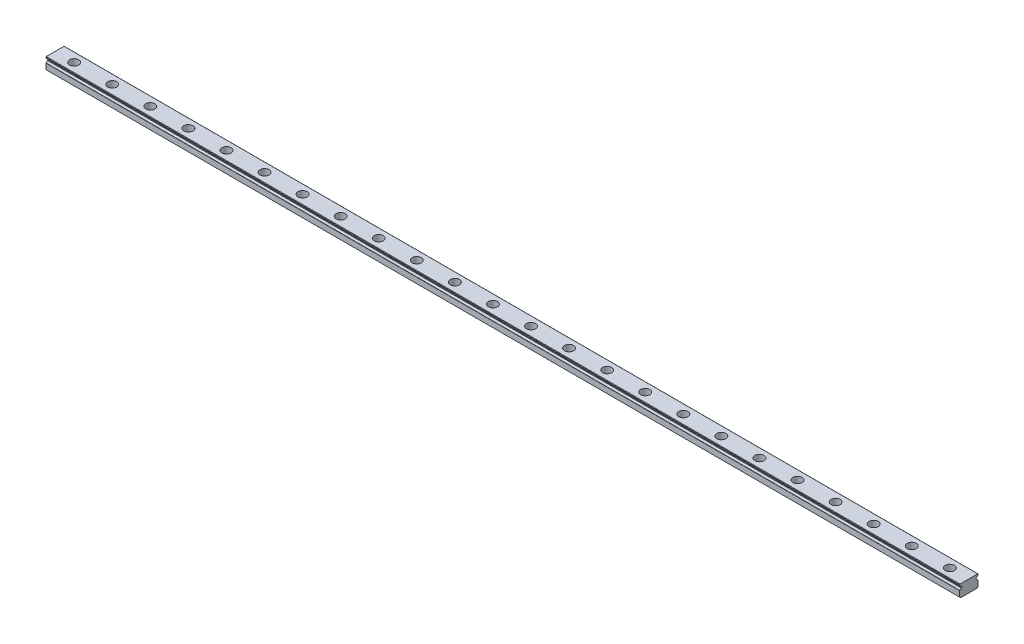
SolidWorks part; units mm, degrees
ref_plane "前视基准面" through (0, 0, 0) normal (0, 0, 1) x (1, 0, 0)
ref_plane "上视基准面" through (0, 0, 0) normal (0, 1, 0) x (1, 0, 0)
ref_plane "右视基准面" through (0, 0, 0) normal (1, 0, 0) x (0, 0, -1)
other "Configuration Table"
ref_plane "基准面1" through (0, 4, 0) normal (0, 1, 0) x (1, 0, 0)
sketch "草图1" plane through (0, 4, 0) normal (0, 1, 0) x (1, 0, 0)
  line L0 (300, -6) -> (300, 6)
  line L1 (300, 6) -> (-300, 6)
  line L2 (-300, 6) -> (-300, -6)
  line L3 (-300, -6) -> (300, -6)
extrude "凸台-拉伸1" add sketch "草图1" against normal blind 8
sketch "草图2" plane through (300, 0, 0) normal (1, 0, 0) x (0, 0, -1)
  line L0 (6, 1.51) -> (6, 2.01)
  line L1 (6, 2.01) -> (4.8, 2.01)
  line L2 (4.8, 1.51) -> (6, 1.51)
  arc A0 (4.8, 2.01) -> (4.8, 1.51) centre (4.8, 1.76) ccw
extrude "切除-拉伸1" cut sketch "草图2" against normal through all
sketch "草图3" plane through (300, 0, 0) normal (1, 0, 0) x (0, 0, -1)
  line L0 (6, 2.01) -> (6, 3.1111)
  line L1 (5.04, 2.01) -> (6, 2.01)
  arc A0 (6, 3.1111) -> (5.04, 2.01) centre (6.4382, 1.76) ccw
extrude "切除-拉伸2" cut sketch "草图3" against normal through all
sketch "草图4" plane through (300, 0, 0) normal (1, 0, 0) x (0, 0, -1)
  line L0 (6, 1.51) -> (5.04, 1.51)
  line L1 (6, 0.4089) -> (6, 1.51)
  arc A0 (5.04, 1.51) -> (6, 0.4089) centre (6.4382, 1.76) ccw
extrude "切除-拉伸3" cut sketch "草图4" against normal through all
sketch "草图5" plane through (300, 0, 0) normal (1, 0, 0) x (0, 0, -1)
  line L0 (-6, 2.01) -> (-6, 1.51)
  line L1 (-6, 1.51) -> (-4.8, 1.51)
  line L2 (-4.8, 2.01) -> (-6, 2.01)
  arc A0 (-4.8, 1.51) -> (-4.8, 2.01) centre (-4.8, 1.76) ccw
extrude "切除-拉伸4" cut sketch "草图5" against normal through all
sketch "草图6" plane through (300, 0, 0) normal (1, 0, 0) x (0, 0, -1)
  line L0 (-6, 1.51) -> (-6, 0.4089)
  line L1 (-5.04, 1.51) -> (-6, 1.51)
  arc A0 (-6, 0.4089) -> (-5.04, 1.51) centre (-6.4382, 1.76) ccw
extrude "切除-拉伸5" cut sketch "草图6" against normal through all
sketch "草图7" plane through (300, 0, 0) normal (1, 0, 0) x (0, 0, -1)
  line L0 (-6, 2.01) -> (-5.04, 2.01)
  line L1 (-6, 3.1111) -> (-6, 2.01)
  arc A0 (-5.04, 2.01) -> (-6, 3.1111) centre (-6.4382, 1.76) ccw
extrude "切除-拉伸6" cut sketch "草图7" against normal through all
hole_wizard "M3 六角头机械螺钉的柱形沉头孔1" positions "草图9" profile "草图8" counterbore size "M3" standard "ANSI Metric"
sketch "草图9" plane through (0, 4, 0) normal (0, 1, 0) x (1, 0, 0)
  point P0 (-287.5, 0)
  point P1 (-262.5, 0)
  point P2 (-237.5, 0)
  point P3 (-212.5, 0)
  point P4 (-187.5, 0)
  point P5 (-162.5, 0)
  point P6 (-137.5, 0)
  point P7 (-112.5, 0)
  point P8 (-87.5, 0)
  point P9 (-62.5, 0)
  point P10 (-37.5, 0)
  point P11 (-12.5, 0)
  point P12 (12.5, 0)
  point P13 (37.5, 0)
  point P14 (62.5, 0)
  point P15 (87.5, 0)
  point P16 (112.5, 0)
  point P17 (137.5, 0)
  point P18 (162.5, 0)
  point P19 (187.5, 0)
  point P20 (212.5, 0)
  point P21 (237.5, 0)
  point P22 (262.5, 0)
  point P23 (287.5, 0)
sketch "草图8" plane through (-287.5, 4, 0) normal (1, 0, 0) x (0, 0, 1)
  line L0 (0, 0) -> (0, 8)
  line L1 (0, 8) -> (1.75, 8)
  line L3 (1.75, 8) -> (1.75, 4.5)
  line L4 (1.75, 4.5) -> (2.9999, 4.5)
  line L5 (2.9999, 4.5) -> (2.9999, 0)
  line L7 (2.9999, 0) -> (0, 0)
  line L11 (0, -6.35) -> (0, 107.95) construction
  dimension "通孔孔直径" = 3.5
  dimension "通孔孔深度" = 8
  dimension "柱形沉头孔直径" = 5.9999
  dimension "柱形沉头孔深度" = 4.5
chamfer "倒角1" distance 0.6 angle 45 2 edges at (0, -4, -6) (0, -4, 6)
fillet "圆角1" radius 0.2 10 edges at (0, 3.1111, -6) (0, 1.51, -5.04) (0, 4, -6) (0, 1.51, 5.04) (0, 2.01, -5.04) (0, 2.01, 5.04) (0, 4, 6) (0, 3.1111, 6) (0, 0.4089, -6) (0, 0.4089, 6)
